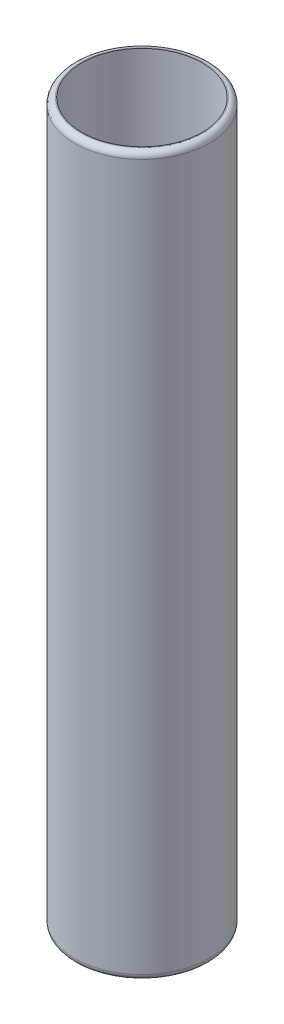
SolidWorks part; units mm, degrees
ref_plane "Front Plane" through (0, 0, 0) normal (0, 0, 1) x (1, 0, 0)
ref_plane "Top Plane" through (0, 0, 0) normal (0, 1, 0) x (1, 0, 0)
ref_plane "Right Plane" through (0, 0, 0) normal (1, 0, 0) x (0, 0, -1)
sketch "Sketch1" plane through (0, 0, 0) normal (0, 1, 0) x (1, 0, 0)
  circle A0 centre (0, 0) radius 14.2875
  circle A1 centre (0, 0) radius 12.8143
  dimension "D1" = 28.575
  dimension "D2" = 1.4732
extrude "Boss-Extrude1" add sketch "Sketch1" along normal blind 152.4
fillet "Fillet1" radius 1.27 2 edges at (0, 152.4, 14.2875) (0, 0, 14.2875)
